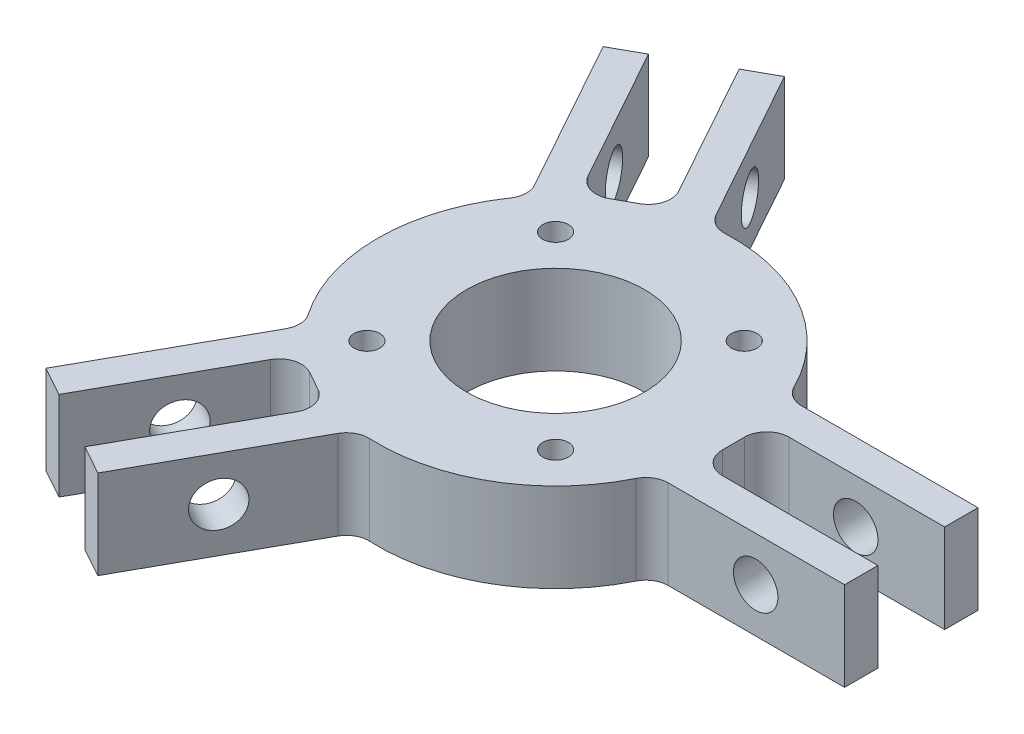
SolidWorks part; units mm, degrees
material "6061 Alloy"
ref_plane "Front Plane" through (0, 0, 0) normal (0, 0, 1) x (1, 0, 0)
ref_plane "Top Plane" through (0, 0, 0) normal (0, 1, 0) x (1, 0, 0)
ref_plane "Right Plane" through (0, 0, 0) normal (1, 0, 0) x (0, 0, -1)
sketch3d "Planning"
  line L0 (0, 0, 0) -> (38.1, 0, 0) construction
  line L1 (38.1, 0, 0) -> (355.6, -190.5, 0) construction
  line L2 (355.6, -190.5, 0) -> (355.6, -203.2, 0) construction
  line L3 (0, 0, 0) -> (-18.503, 0, 33.3054) construction
  line L4 (0, 0, 0) -> (-18.503, 0, -33.3054) construction
  line L5 (-18.503, 0, 33.3054) -> (-127, -190.5, 228.6) construction
  line L6 (-127, -190.5, 228.6) -> (-127, -203.2, 228.6) construction
  line L7 (-18.503, 0, -33.3054) -> (-127, -190.5, -228.6) construction
  line L8 (-127, -190.5, -228.6) -> (-127, -203.2, -228.6) construction
  line L9 (-18.503, 0, -33.3054) -> (-18.503, 0, 33.3054) construction
  line L10 (-127, -203.2, -228.6) -> (-127, -203.2, 228.6) construction
  line L11 (355.6, -203.2, 0) -> (-127, -203.2, 0) construction
  line L12 (0, 0, 0) -> (0, -203.2, 0) construction
  point P11 (-18.503, 0, 0)
  dimension "D1" = 38.1
  dimension "D2" = 12.7
  dimension "D3" = 203.2
  dimension "D4" = 482.6
  dimension "D5" = 127
  dimension "D6" = 457.2
sketch "Sketch1" plane through (0, 0, 0) normal (0, 1, 0) x (1, 0, 0)
  line L0 (0, 0) -> (25.4, 0) construction
  line L1 (25.4, 4.7625) -> (25.4, -4.7625)
  line L2 (25.4, -4.7625) -> (50.8, -4.7625)
  line L3 (50.8, -4.7625) -> (50.8, -9.525)
  line L4 (25.4, 4.7625) -> (50.8, 4.7625)
  line L5 (13.4704, 13.4704) -> (-13.4704, -13.4704) construction
  line L6 (13.4704, -13.4704) -> (-13.4704, 13.4704) construction
  line L7 (50.8, 4.7625) -> (50.8, 9.525)
  line L8 (0, 0) -> (-12.3353, -22.2036) construction
  line L9 (38.1, 4.7625) -> (38.1, -4.7625) construction
  line L10 (-32.997, -39.7814) -> (-28.8338, -42.0943)
  line L11 (-28.8338, -42.0943) -> (-16.4985, -19.8907)
  line L12 (-16.4985, -19.8907) -> (-8.1722, -24.5165)
  line L13 (-8.1722, -24.5165) -> (-20.5075, -46.7201)
  line L14 (-20.5075, -46.7201) -> (-16.3443, -49.0329)
  line L15 (-16.3443, -49.0329) -> (-3.1088, -25.209)
  line L16 (50.8, -9.525) -> (23.5464, -9.525)
  line L17 (-32.997, -39.7814) -> (-19.7615, -15.9575)
  line L18 (0, 0) -> (-12.3353, 22.2036) construction
  line L19 (-16.3443, 49.0329) -> (-3.1088, 25.209)
  line L20 (-20.5075, 46.7201) -> (-16.3443, 49.0329)
  line L21 (-8.1722, 24.5165) -> (-20.5075, 46.7201)
  line L22 (-16.4985, 19.8907) -> (-8.1722, 24.5165)
  line L23 (-28.8338, 42.0943) -> (-16.4985, 19.8907)
  line L24 (-32.997, 39.7814) -> (-28.8338, 42.0943)
  line L25 (-32.997, 39.7814) -> (-19.7615, 15.9575)
  line L26 (50.8, 9.525) -> (23.5464, 9.525)
  line L27 (0, 0) -> (-18.503, 33.3054) construction
  circle A0 centre (0, 0) radius 12.7
  circle A1 centre (-13.4704, 13.4704) radius 1.8288
  circle A2 centre (13.4704, 13.4704) radius 1.8288
  circle A3 centre (13.4704, -13.4704) radius 1.8288
  circle A4 centre (-13.4704, -13.4704) radius 1.8288
  arc A5 (-3.1088, -25.209) -> (23.5464, -9.525) centre (0, 0) ccw
  arc A6 (-3.1088, 25.209) -> (23.5464, 9.525) centre (0, 0) cw
  arc A7 (-19.7615, 15.9575) -> (-19.7615, -15.9575) centre (0, 0) ccw
  dimension "D3" = 25.4
  dimension "D5" = 3.6576
  dimension "D8" = 25.4
  dimension "D1" = 9.525
  dimension "D2" = 25.4
  dimension "D4" = 38.1
  dimension "D6" = 4.7625
extrude "Boss-Extrude1" add sketch "Sketch1" along normal mid plane 12.7
hole_wizard "1/4 (0.25) Diameter Hole1" positions "3DSketch1" profile "Sketch4" hole size "1/4" standard "ANSI Inch"
sketch3d "3DSketch1"
  line L0 (25.4, -6.35, 4.7625) -> (50.8, 6.35, 4.7625) construction
  line L3 (25.4, -6.35, -4.7625) -> (50.8, 6.35, -4.7625) construction
  line L6 (-8.1722, -6.35, -24.5165) -> (-20.5075, 6.35, -46.7201) construction
  line L9 (-16.4985, -6.35, -19.8907) -> (-28.8338, 6.35, -42.0943) construction
  line L12 (-8.1722, -6.35, 24.5165) -> (-20.5075, 6.35, 46.7201) construction
  line L15 (-28.8338, 6.35, 42.0943) -> (-16.4985, -6.35, 19.8907) construction
  point P0 (38.1, 0, -4.7625)
  point P2 (-14.3398, 0, -35.6183)
  point P4 (-22.6662, 0, 30.9925)
  point P6 (-14.3398, 0, 35.6183)
  point P8 (-22.6662, 0, -30.9925)
  point P10 (38.1, 0, 4.7625)
sketch "Sketch4" plane through (38.1, 0, -4.7625) normal (1, 0, 0) x (0, -1, 0)
  line L0 (0, 0) -> (0, 4.7625)
  line L1 (0, 4.7625) -> (3.175, 4.7625)
  line L2 (3.175, 4.7625) -> (3.175, 0)
  line L5 (3.175, 0) -> (0, 0)
  line L11 (0, -6.35) -> (0, 107.95) construction
  dimension "Thru Hole Dia." = 6.35
  dimension "Thru Hole Depth" = 4.7625
fillet "Fillet1" radius 3.175 12 edges at (-19.7615, 0, 15.9575) (-16.4985, 0, 19.8907) (-8.1722, 0, 24.5165) (-3.1088, 0, 25.209) (23.5464, 0, 9.525) (25.4, 0, -4.7625) (23.5464, 0, -9.525) (-3.1088, 0, -25.209) (-8.1722, 0, -24.5165) (-16.4985, 0, -19.8907) (-19.7615, 0, -15.9575) (25.4, 0, 4.7625)
